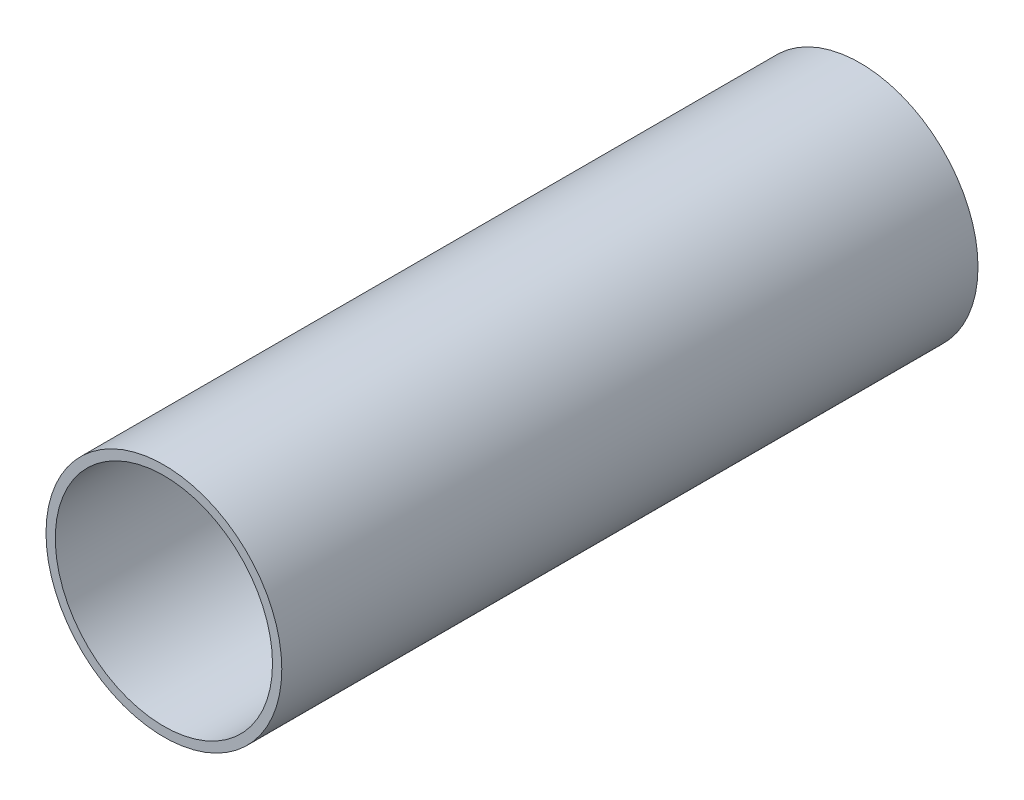
SolidWorks part; units mm, degrees
ref_plane "Plano frontal" through (0, 0, 0) normal (0, 0, 1) x (1, 0, 0)
ref_plane "Plano superior" through (0, 0, 0) normal (0, 1, 0) x (1, 0, 0)
ref_plane "Plano direito" through (0, 0, 0) normal (1, 0, 0) x (0, 0, -1)
sketch "Esboço1" plane through (0, 0, 0) normal (0, 0, 1) x (1, 0, 0)
  circle A0 centre (0, 0) radius 25.4
  circle A1 centre (0, 0) radius 23.4
  dimension "D1" = 2
  dimension "D2" = 50.8
extrude "Ressalto-extrusão1" add sketch "Esboço1" along normal blind 150
